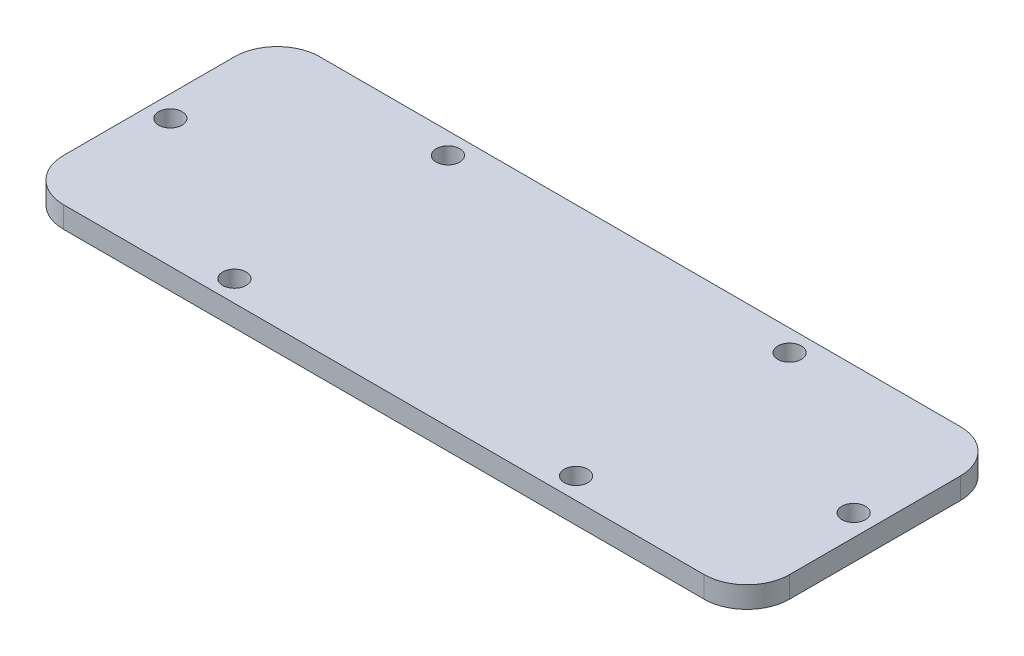
SolidWorks part; units mm, degrees
ref_plane "Front Plane" through (0, 0, 0) normal (0, 0, 1) x (1, 0, 0)
ref_plane "Top Plane" through (0, 0, 0) normal (0, 1, 0) x (1, 0, 0)
ref_plane "Right Plane" through (0, 0, 0) normal (1, 0, 0) x (0, 0, -1)
sketch "Sketch1" plane through (0, 0, 0) normal (0, 1, 0) x (1, 0, 0)
  line L1 (10, 0) -> (160, 0)
  line L2 (0, 10) -> (0, 50)
  line L3 (10, 60) -> (160, 60)
  line L4 (170, 10) -> (170, 50)
  arc A0 (160, 0) -> (170, 10) centre (160, 10) ccw
  arc A1 (0, 50) -> (10, 60) centre (10, 50) cw
  arc A2 (160, 60) -> (170, 50) centre (160, 50) cw
  arc A3 (10, 0) -> (0, 10) centre (10, 10) cw
  point P9 (0, 60)
  point P12 (170, 60)
  point P15 (0, 0)
  dimension "D3" = 10
  dimension "D1" = 60
  dimension "D2" = 170
extrude "Boss-Extrude2" add sketch "Sketch1" along normal blind 5
sketch "Sketch3" plane through (0, 5, 0) normal (0, 1, 0) x (1, 0, 0)
  line L0 (160, 60) -> (10, 60) construction
  line L1 (0, 50) -> (0, 10) construction
  line L2 (10, 0) -> (160, 0) construction
  circle A0 centre (5, 30) radius 2.75
  circle A1 centre (45, 55) radius 2.75
  circle A2 centre (125, 55) radius 2.75
  circle A3 centre (165, 30) radius 2.75
  circle A4 centre (125, 5) radius 2.75
  circle A5 centre (45, 5) radius 2.75
  point P0 (5, 30)
  point P1 (45, 55)
  point P2 (45, 5)
  point P3 (125, 55)
  point P4 (125, 5)
  point P5 (165, 30)
  point P13 (85, 60)
  point P21 (0, 30)
  dimension "D7" = 5.5
  dimension "D1" = 80
  dimension "D2" = 40
  dimension "D3" = 5
  dimension "D4" = 160
  dimension "D5" = 50
  dimension "D6" = 5
extrude "Cut-Extrude1" cut sketch "Sketch3" against normal blind 5
